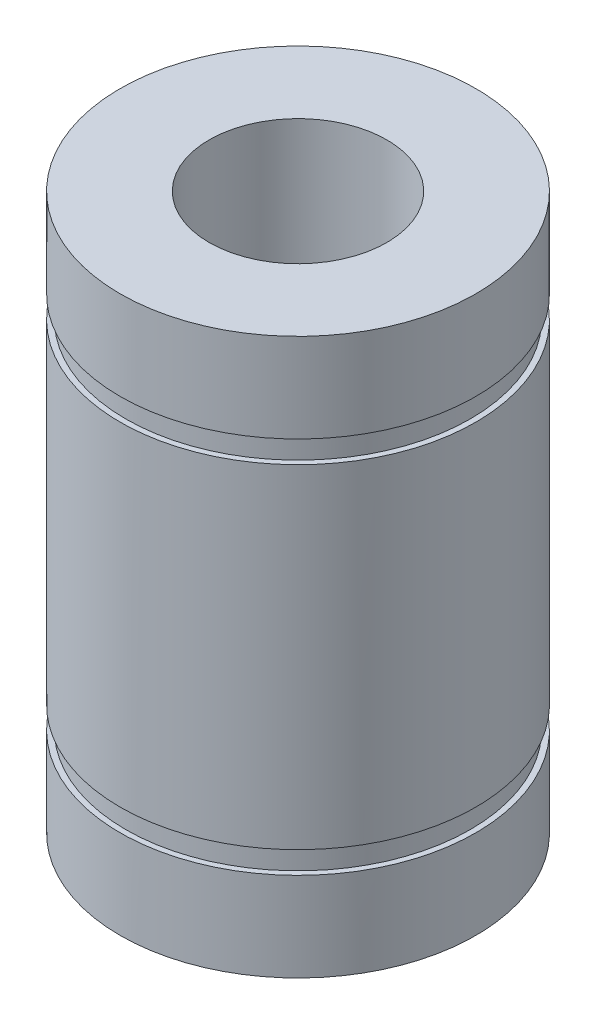
SolidWorks part; units mm, degrees
ref_plane "Front Plane" through (0, 0, 0) normal (0, 0, 1) x (1, 0, 0)
ref_plane "Top Plane" through (0, 0, 0) normal (0, 1, 0) x (1, 0, 0)
ref_plane "Right Plane" through (0, 0, 0) normal (1, 0, 0) x (0, 0, -1)
sketch "Sketch1" plane through (0, 0, 0) normal (0, 1, 0) x (1, 0, 0)
  circle A0 centre (0, 0) radius 8
  circle A1 centre (0, 0) radius 4
  dimension "D1" = 16
  dimension "D2" = 8
extrude "Boss-Extrude1" add sketch "Sketch1" along normal blind 25
ref_plane "Plane1" through (0, 12.5, 0) normal (0, -1, 0) x (-1, 0, 0)
sketch "Sketch2" plane through (0, 0, 0) normal (0, 0, 1) x (1, 0, 0)
  line L0 (-8, 25) -> (-8, 0) construction
  line L1 (-9, 21) -> (-7.75, 21)
  line L2 (-9, 21) -> (-9, 20)
  line L3 (-9, 20) -> (-7.75, 20)
  line L4 (-7.75, 21) -> (-7.75, 20)
  line L5 (8, 25) -> (-8, 25) construction
  line L6 (-8.8, 12.5) -> (8.8, 12.5) construction
  line L7 (-7.75, 4) -> (-7.75, 5)
  line L8 (-9, 5) -> (-7.75, 5)
  line L9 (-9, 4) -> (-9, 5)
  line L10 (-9, 4) -> (-7.75, 4)
  point P6 (-8.375, 21)
  dimension "D1" = 0.25
  dimension "D2" = 1
  dimension "D3" = 1
  dimension "D4" = 4
revolve "Cut-Revolve1" cut sketch "Sketch2" angle 360 about axis through (0, 25, 0) along (0, -1, 0)
